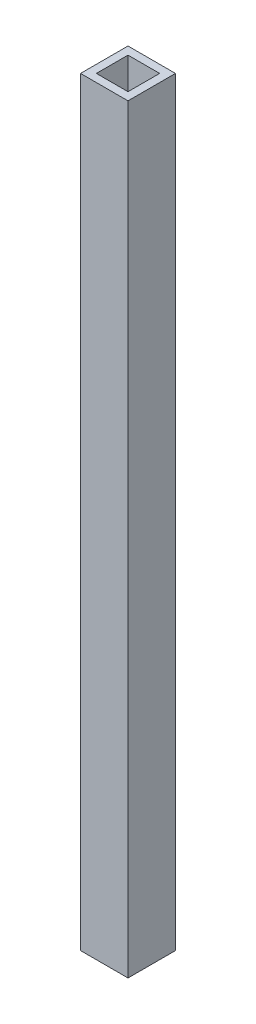
SolidWorks part; units mm, degrees
ref_plane "Front Plane" through (0, 0, 0) normal (0, 0, 1) x (1, 0, 0)
ref_plane "Top Plane" through (0, 0, 0) normal (0, 1, 0) x (1, 0, 0)
ref_plane "Right Plane" through (0, 0, 0) normal (1, 0, 0) x (0, 0, -1)
sketch "Sketch1" plane through (0, 0, 0) normal (0, 1, 0) x (1, 0, 0)
  line L1 (0, 0) -> (19.05, 0)
  line L2 (0, 0) -> (0, 19.05)
  line L3 (0, 19.05) -> (19.05, 19.05)
  line L4 (19.05, 0) -> (19.05, 19.05)
  dimension "D1" = 19.05
  dimension "D2" = 19.05
extrude "Boss-Extrude1" add sketch "Sketch1" along normal blind 304.8
sketch "Sketch2" plane through (0, 304.8, 0) normal (0, 1, 0) x (1, 0, 0)
  line L0 (19.05, 0) -> (19.05, 19.05) construction
  line L1 (3.175, 15.875) -> (15.875, 15.875)
  line L2 (3.175, 15.875) -> (3.175, 3.175)
  line L3 (3.175, 3.175) -> (15.875, 3.175)
  line L4 (15.875, 15.875) -> (15.875, 3.175)
  line L5 (19.05, 19.05) -> (0, 19.05) construction
  dimension "D1" = 12.7
  dimension "D2" = 12.7
  dimension "D3" = 3.175
  dimension "D4" = 3.175
extrude "Cut-Extrude1" cut sketch "Sketch2" against normal blind 406.4
